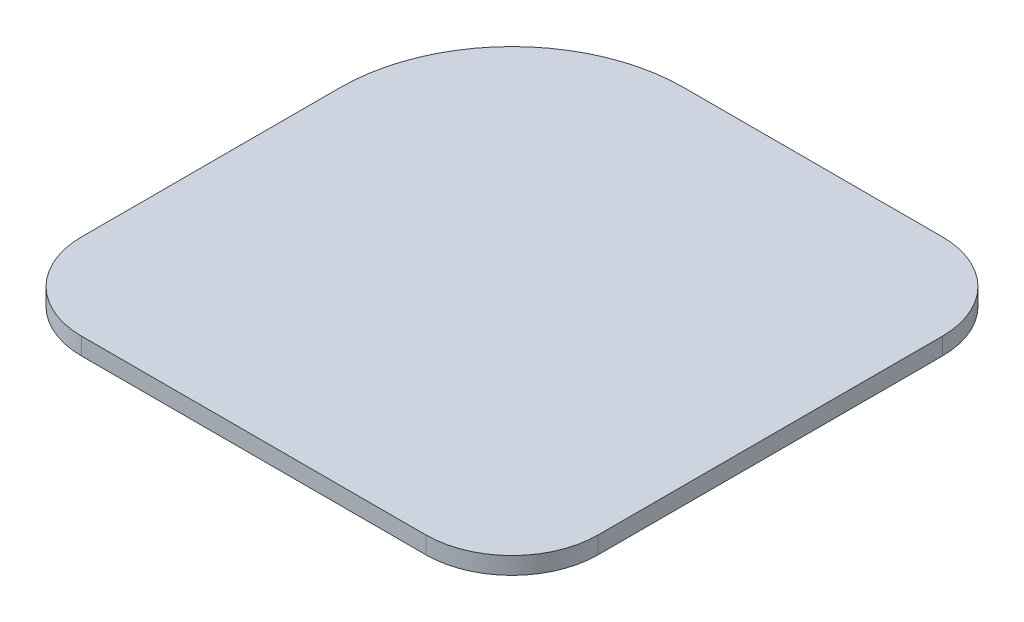
SolidWorks part; units mm, degrees
ref_plane "Front Plane" through (0, 0, 0) normal (0, 0, 1) x (1, 0, 0)
ref_plane "Top Plane" through (0, 0, 0) normal (0, 1, 0) x (1, 0, 0)
ref_plane "Right Plane" through (0, 0, 0) normal (1, 0, 0) x (0, 0, -1)
sketch "Sketch2" plane through (0, 0, 0) normal (0, 1, 0) x (1, 0, 0)
  line L1 (-10, 30) -> (20, 30)
  line L2 (-30, 10) -> (-30, -20)
  line L3 (-20, -30) -> (20, -30)
  line L4 (30, 20) -> (30, -20)
  line L5 (-30, 30) -> (30, -30) construction
  line L6 (-30, -30) -> (30, 30) construction
  arc A0 (-10, 30) -> (-30, 10) centre (-10, 10) ccw
  arc A1 (-30, -20) -> (-20, -30) centre (-20, -20) ccw
  arc A2 (20, -30) -> (30, -20) centre (20, -20) ccw
  arc A3 (20, 30) -> (30, 20) centre (20, 20) cw
  point P0 (0, 0)
  dimension "D3" = 20
  dimension "D4" = 10
  dimension "D1" = 60
  dimension "D2" = 60
extrude "Boss-Extrude1" add sketch "Sketch2" along normal blind 2
